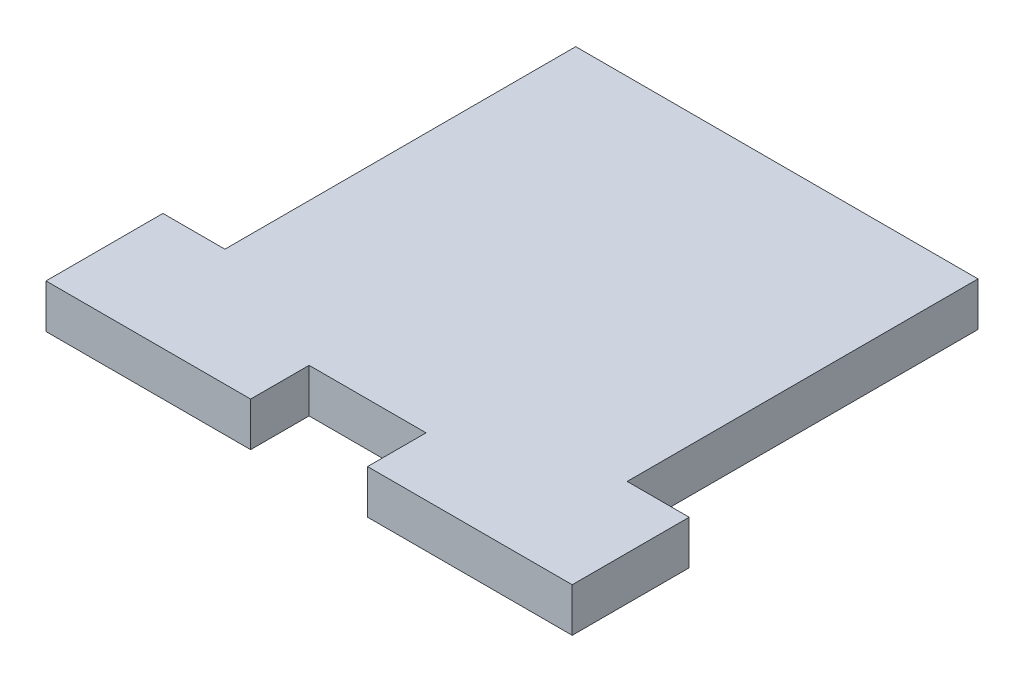
SolidWorks part; units mm, degrees
ref_plane "Front Plane" through (0, 0, 0) normal (0, 0, 1) x (1, 0, 0)
ref_plane "Top Plane" through (0, 0, 0) normal (0, 1, 0) x (1, 0, 0)
ref_plane "Right Plane" through (0, 0, 0) normal (1, 0, 0) x (0, 0, -1)
sketch "Sketch1" plane through (0, 0, 0) normal (0, 1, 0) x (1, 0, 0)
  line L0 (0, 0) -> (-68.8, 0)
  line L1 (-68.8, 0) -> (-68.8, -60)
  line L2 (-68.8, -60) -> (-79.4, -60)
  line L3 (-79.4, -60) -> (-79.4, -80)
  line L4 (-79.4, -80) -> (-44.4, -80)
  line L8 (-24.4, -80) -> (10.6, -80)
  line L9 (10.6, -80) -> (10.6, -60)
  line L10 (10.6, -60) -> (0, -60)
  line L11 (0, -60) -> (0, 0)
  line L12 (-44.4, -80) -> (-44.4, -70)
  line L13 (-44.4, -70) -> (-24.4, -70)
  line L14 (-24.4, -70) -> (-24.4, -80)
  dimension "D2" = 60
  dimension "D3" = 35
  dimension "D4" = 20
  dimension "D5" = 10
  dimension "D6" = 20
  dimension "D7" = 10.6
  dimension "D8" = 20
  dimension "D9" = 35
  dimension "D10" = 10.6
  dimension "D11" = 80
extrude "Boss-Extrude1" add sketch "Sketch1" against normal blind 7.5
